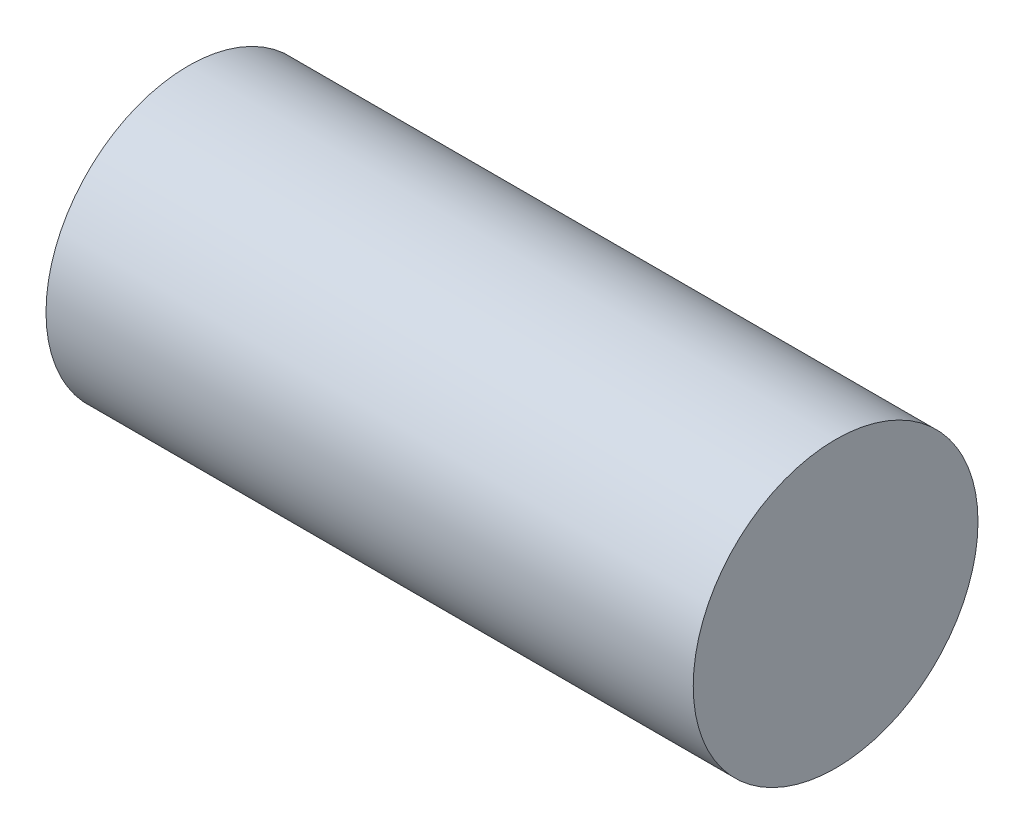
SolidWorks part; units mm, degrees
ref_plane "Front Plane" through (0, 0, 0) normal (0, 0, 1) x (1, 0, 0)
ref_plane "Top Plane" through (0, 0, 0) normal (0, 1, 0) x (1, 0, 0)
ref_plane "Right Plane" through (0, 0, 0) normal (1, 0, 0) x (0, 0, -1)
sketch "Sketch1" plane through (0, 0, 0) normal (1, 0, 0) x (0, 0, -1)
  circle A0 centre (0, 0) radius 11
  dimension "D1" = 22
extrude "Boss-Extrude1" add sketch "Sketch1" along normal blind 50
